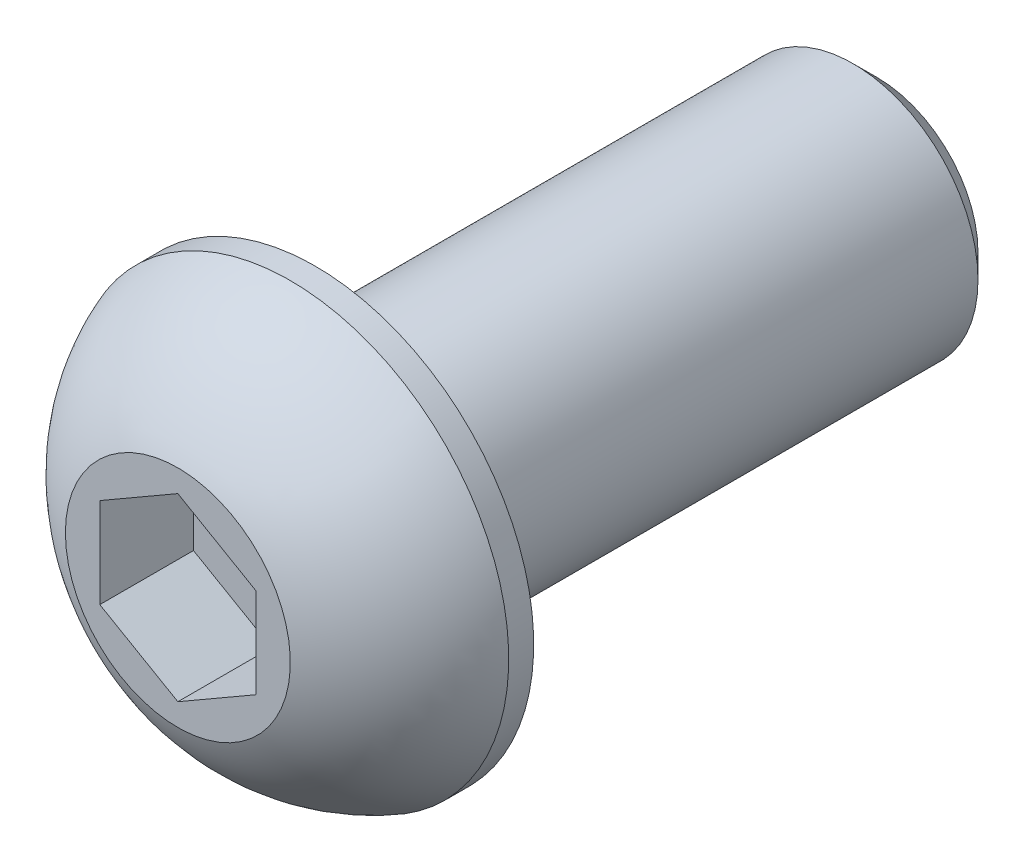
SolidWorks part; units mm, degrees
ref_plane "Front" through (0, 0, 0) normal (0, 0, 1) x (1, 0, 0)
ref_plane "Top" through (0, 0, 0) normal (0, 1, 0) x (1, 0, 0)
ref_plane "Right" through (0, 0, 0) normal (1, 0, 0) x (0, 0, -1)
ref_plane "Plane1" through (0, 0, 0) normal (0, -1, 0) x (1, 0, 0)
sketch "Sketch1" plane through (0, 0, 0) normal (0, -1, 0) x (1, 0, 0)
  line L0 (3.603, 4.4) -> (0, 4.4)
  line L1 (0, 4.4) -> (0, 0)
  line L2 (0, 0) -> (7, 0)
  line L3 (7, 0) -> (7, 0.8)
  line L4 (0, 4.4) -> (0, 0) construction
  arc A0 (7, 0.8) -> (3.603, 4.4) centre (1.1296, -1.3367) ccw
revolve "Revolve1" add sketch "Sketch1" angle 360 about L4
sketch "Sketch2" plane through (0, 0, 0) normal (0, 0, -1) x (-1, 0, 0)
  circle A0 centre (0, 0) radius 4
extrude "Boss-Extrude1" add sketch "Sketch2" along normal blind 18
sketch "Sketch3" plane through (0, 0, 4.4) normal (0, 0, 1) x (1, 0, 0)
  line L0 (2.5, -1.4434) -> (2.5, 1.4434)
  line L1 (2.5, 1.4434) -> (0, 2.8868)
  line L2 (0, 2.8868) -> (-2.5, 1.4434)
  line L3 (-2.5, 1.4434) -> (-2.5, -1.4434)
  line L4 (-2.5, -1.4434) -> (0, -2.8868)
  line L5 (0, -2.8868) -> (2.5, -1.4434)
extrude "Cut-Extrude1" cut sketch "Sketch3" against normal blind 3
chamfer "Chamfer1" distance 0.7668 angle 45 1 edges at (-4, 0, -18)
fillet "Fillet1" radius 0.4 1 edges at (-4, 0, 0)
